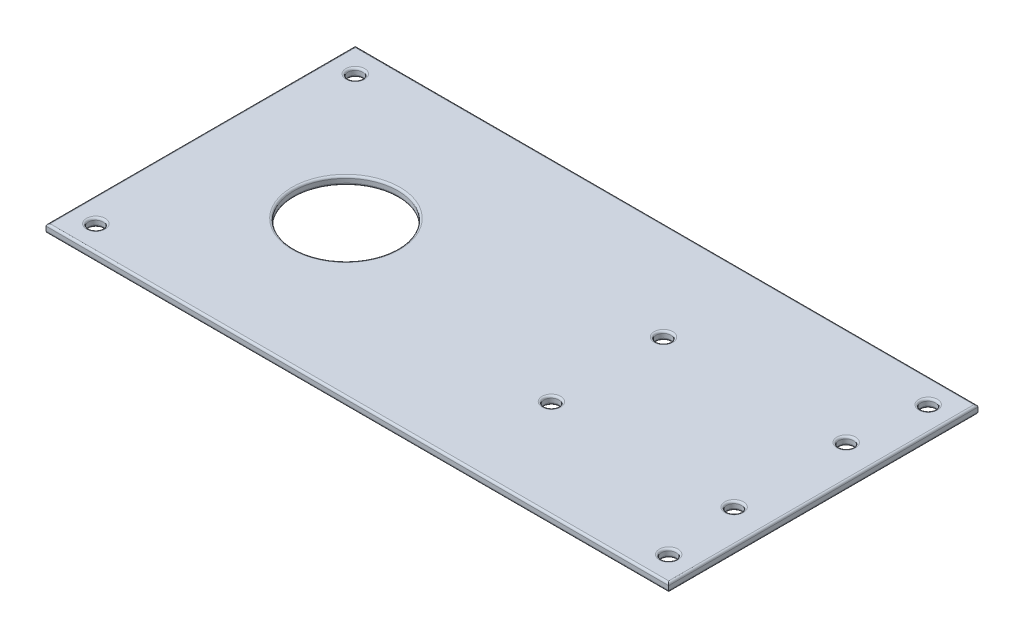
SolidWorks part; units mm, degrees
ref_plane "Front Plane" through (0, 0, 0) normal (0, 0, 1) x (1, 0, 0)
ref_plane "Top Plane" through (0, 0, 0) normal (0, 1, 0) x (1, 0, 0)
ref_plane "Right Plane" through (0, 0, 0) normal (1, 0, 0) x (0, 0, -1)
sketch "Sketch1" plane through (0, 0, 0) normal (0, 1, 0) x (1, 0, 0)
  line L0 (0, 37.25) -> (5, 37.25) construction
  line L1 (0, 0) -> (150, 0)
  line L2 (0, 0) -> (0, 74.5)
  line L3 (0, 74.5) -> (150, 74.5)
  line L4 (150, 0) -> (150, 74.5)
  line L5 (6, 74.5) -> (6, 68.5) construction
  line L6 (6, 68.5) -> (0, 68.5) construction
  line L7 (144, 0) -> (144, 6) construction
  line L8 (144, 6) -> (150, 6) construction
  line L9 (150, 68.5) -> (144, 68.5) construction
  line L10 (144, 68.5) -> (144, 74.5) construction
  line L11 (5, 37.25) -> (35, 37.25) construction
  line L12 (0, 6) -> (6, 6) construction
  line L13 (6, 6) -> (6, 0) construction
  line L14 (150, 37.25) -> (142, 37.25) construction
  line L15 (142, 37.25) -> (142, 50.75) construction
  line L16 (142, 50.75) -> (98, 50.75) construction
  line L17 (98, 50.75) -> (98, 23.75) construction
  line L18 (98, 23.75) -> (142, 23.75) construction
  line L19 (142, 23.75) -> (142, 37.25) construction
  circle A2 centre (144, 6) radius 1.75
  circle A3 centre (144, 68.5) radius 1.75
  circle A4 centre (35, 37.25) radius 12.5
  circle A5 centre (6, 68.5) radius 1.75
  circle A6 centre (6, 6) radius 1.75
  circle A7 centre (98, 50.75) radius 1.75
  circle A8 centre (142, 50.75) radius 1.75
  circle A9 centre (142, 23.75) radius 1.75
  circle A10 centre (98, 23.75) radius 1.75
  dimension "D5" = 44
  dimension "D7" = 3.5
  dimension "D8" = 25
  dimension "D11" = 3.5
  dimension "D1" = 74.5
  dimension "D2" = 150
  dimension "D3" = 5
  dimension "D4" = 8
  dimension "D6" = 6
  dimension "D9" = 30
  dimension "D10" = 27
extrude "Boss-Extrude1" add sketch "Sketch1" along normal blind 2
fillet "Fillet1" radius 0.5 26 edges at (144, 0, -66.75) (75, 0, 0) (150, 0, -37.25) (75, 0, -74.5) (0, 0, -37.25) (144, 0, -4.25) (144, 2, -66.75) (144, 2, -4.25) (75, 2, -74.5) (150, 2, -37.25) (75, 2, 0) (0, 2, -37.25) (35, 0, -24.75) (35, 2, -24.75) (6, 0, -4.25) (6, 0, -66.75) (6, 2, -4.25) (6, 2, -66.75) (98, 0, -22) (142, 0, -49) (98, 0, -49) (142, 0, -22) (98, 2, -22) (142, 2, -22) (142, 2, -49) (98, 2, -49)
